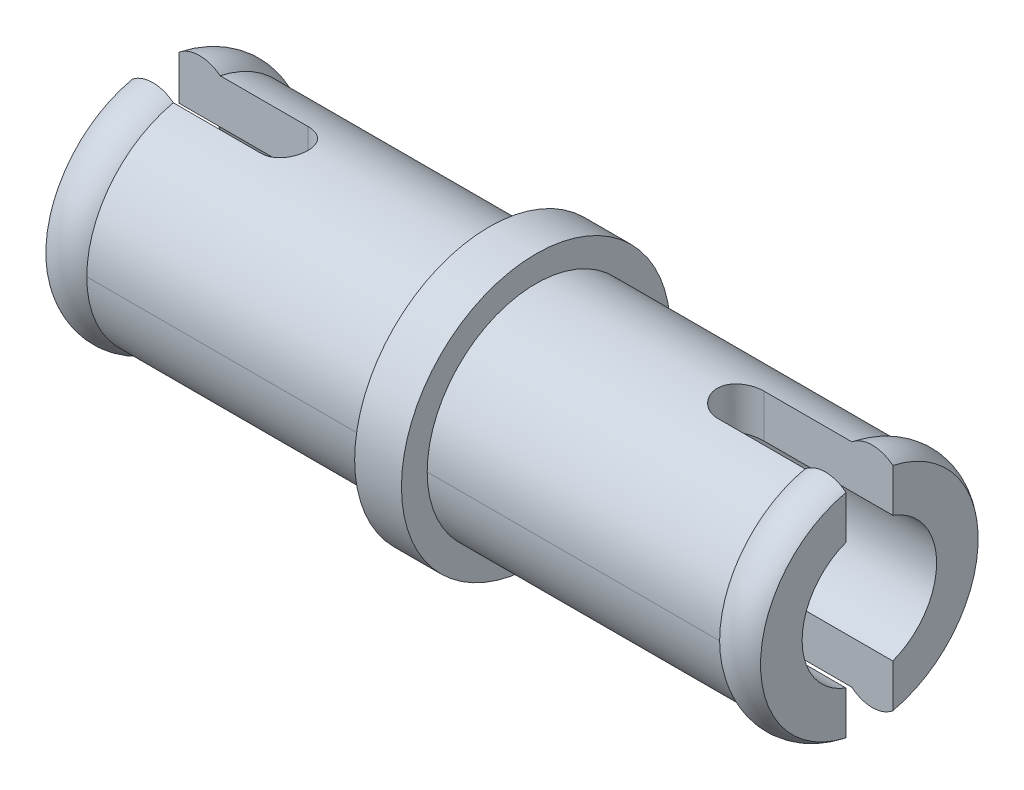
SolidWorks part; units mm, degrees
ref_plane "Front" through (0, 0, 0) normal (0, 0, 1) x (1, 0, 0)
ref_plane "Top" through (0, 0, 0) normal (0, 1, 0) x (1, 0, 0)
ref_plane "Right" through (0, 0, 0) normal (1, 0, 0) x (0, 0, -1)
sketch "Sketch1" plane through (0, 0, 0) normal (1, 0, 0) x (0, 0, -1)
  circle A0 centre (0, 0) radius 2.3622
  dimension "D1" = 4.7244
extrude "Base-Extrude" add sketch "Sketch1" along normal blind 7.239
sketch "Sketch3" plane through (0, 0, 0) normal (-1, 0, 0) x (0, 0, 1)
  circle A0 centre (0, 0) radius 2.921
  dimension "D1" = 5.842
extrude "Boss-Extrude1" add sketch "Sketch3" along normal blind 1.016
sketch "Sketch4" plane through (-1.016, 0, 0) normal (-1, 0, 0) x (0, 0, 1)
  circle A0 centre (0, 0) radius 2.3876
  dimension "D1" = 4.7752
extrude "Boss-Extrude2" add sketch "Sketch4" along normal blind 7.239
split line "Split Line1"
ref_plane "Plane1" through (-0.508, 0, 0) normal (1, 0, 0) x (0, 0, -1)
sketch "Sketch6" plane through (0, 0, 0) normal (0, 1, 0) x (1, 0, 0)
  line L0 (-1.016, 2.3876) -> (-8.255, 2.3876) construction
  line L1 (0, 0) -> (-8.8014, 0) construction
  line L2 (-8.255, 2.3876) -> (-7.366, 2.3876)
  arc A0 (-8.255, 2.3876) -> (-7.366, 2.3876) centre (-7.8105, 1.8156) cw
  dimension "D1" = 0.889
  dimension "D2" = 5.08
revolve "Boss-Revolve2" add sketch "Sketch6" angle 360 about L1
sketch "Sketch9" plane through (0, 0, 0) normal (0, 1, 0) x (1, 0, 0)
  line L0 (7.239, 2.3622) -> (0, 2.3622) construction
  line L1 (6.35, 2.3622) -> (7.239, 2.3622)
  line L2 (0, 0) -> (7.54, 0) construction
  arc A0 (7.239, 2.3622) -> (6.35, 2.3622) centre (6.7945, 1.8156) ccw
  dimension "D1" = 0.889
revolve "Boss-Revolve3" add sketch "Sketch9" angle 360 about L2
sketch "Sketch7" plane through (-8.255, 0, 0) normal (-1, 0, 0) x (0, 0, 1)
  circle A0 centre (0, 0) radius 1.4605
  dimension "D1" = 2.921
extrude "Cut-Extrude2" cut sketch "Sketch7" against normal through all
sketch "Sketch8" plane through (0, 0, 0) normal (0, 1, 0) x (1, 0, 0)
  line L0 (0, 0) -> (-8.8999, 0) construction
  line L1 (-8.255, 0.508) -> (-5.461, 0.508)
  line L3 (-5.461, -0.508) -> (-8.255, -0.508)
  line L4 (-8.255, -0.508) -> (-8.255, 0.508)
  line L5 (-8.255, -2.3876) -> (-8.255, 2.3876) construction
  arc A0 (-5.461, 0.508) -> (-5.461, -0.508) centre (-5.461, 0) cw
  dimension "D1" = 1.016
  dimension "D2" = 2.794
extrude "Cut-Extrude4" cut sketch "Sketch8" against normal through all and the other way through all
mirror "Mirror7" about plane through (-0.508, 0, 0) normal (1, 0, 0) of "Cut-Extrude4"
